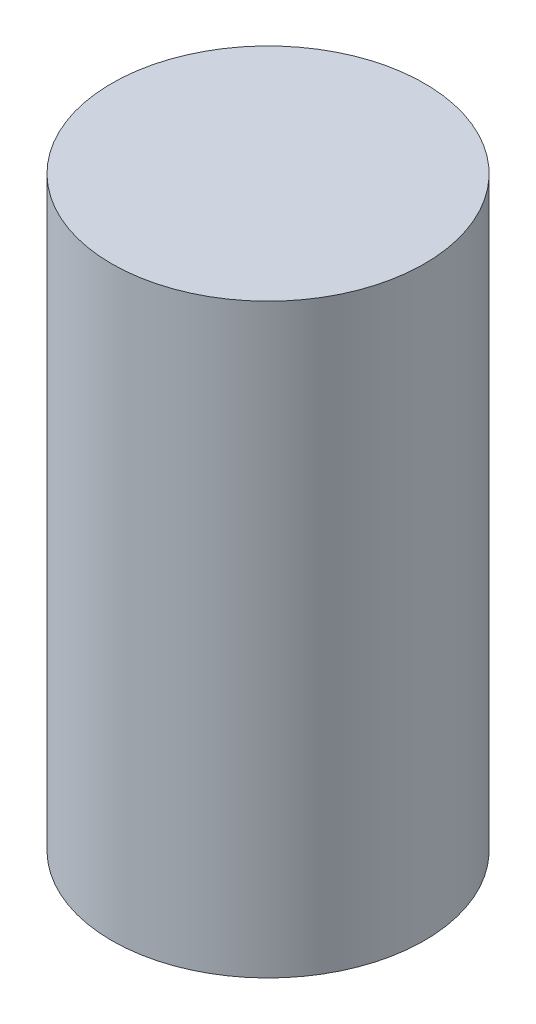
SolidWorks part; units mm, degrees
ref_plane "Front Plane" through (0, 0, 0) normal (0, 0, 1) x (1, 0, 0)
ref_plane "Top Plane" through (0, 0, 0) normal (0, 1, 0) x (1, 0, 0)
ref_plane "Right Plane" through (0, 0, 0) normal (1, 0, 0) x (0, 0, -1)
sketch "Sketch1" plane through (0, 0, 0) normal (0, 1, 0) x (1, 0, 0)
  circle A0 centre (0, 0) radius 69.85
  dimension "D1" = 139.7
extrude "Boss-Extrude1" add sketch "Sketch1" along normal blind 261.874
